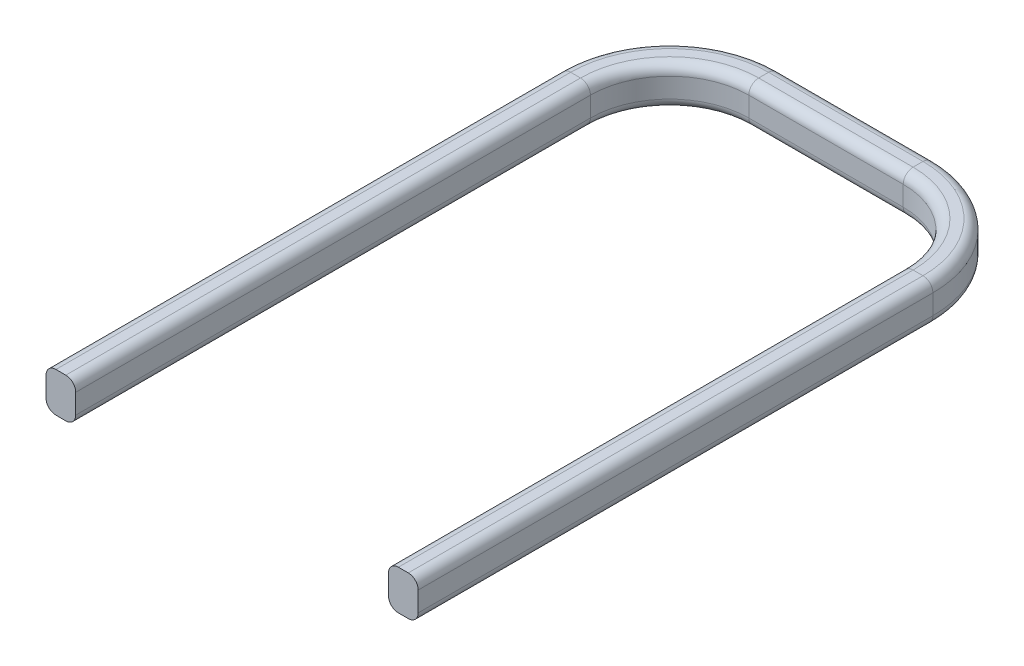
SolidWorks part; units mm, degrees
ref_plane "Front Plane" through (0, 0, 0) normal (0, 0, 1) x (1, 0, 0)
ref_plane "Top Plane" through (0, 0, 0) normal (0, 1, 0) x (1, 0, 0)
ref_plane "Right Plane" through (0, 0, 0) normal (1, 0, 0) x (0, 0, -1)
sketch "Sketch1" plane through (0, 0, 0) normal (0, 1, 0) x (1, 0, 0)
  line L0 (-3.95, 0) -> (-3.95, 13)
  line L1 (-1.95, 15) -> (1.95, 15)
  line L2 (3.95, 13) -> (3.95, 0)
  arc A0 (1.95, 15) -> (3.95, 13) centre (1.95, 13) cw
  arc A1 (-3.95, 13) -> (-1.95, 15) centre (-1.95, 13) cw
  point P3 (0, 0)
  point P5 (0, 15)
  point P11 (-3.95, 15)
  dimension "D3" = 2
  dimension "D1" = 3.95
  dimension "D2" = 15
sketch "Sketch2" plane through (0, 0, 0) normal (0, 0, 1) x (1, 0, 0)
  line L1 (-3.95, 0) -> (-4.7, 0)
  line L2 (-3.95, 0) -> (-3.95, 1)
  line L3 (-3.95, 1) -> (-4.7, 1)
  line L4 (-4.7, 0) -> (-4.7, 1)
  dimension "D1" = 1
  dimension "D2" = 0.75
sweep "Sweep1" add profiles "Sketch2" path "Sketch1"
fillet "Fillet1" radius 0.25 20 edges at (-4.7, 0, -6.5) (-3.8945, 0, -14.9445) (0, 0, -15.75) (3.8945, 0, -14.9445) (3.95, 0, -6.5) (3.3642, 0, -14.4142) (0, 0, -15) (-3.3642, 0, -14.4142) (4.7, 1, -6.5) (3.8945, 1, -14.9445) (0, 1, -15.75) (-3.8945, 1, -14.9445) (3.95, 1, -6.5) (3.3642, 1, -14.4142) (0, 1, -15) (-3.3642, 1, -14.4142) (4.7, 0, -6.5) (-3.95, 0, -6.5) (-4.7, 1, -6.5) (-3.95, 1, -6.5)
